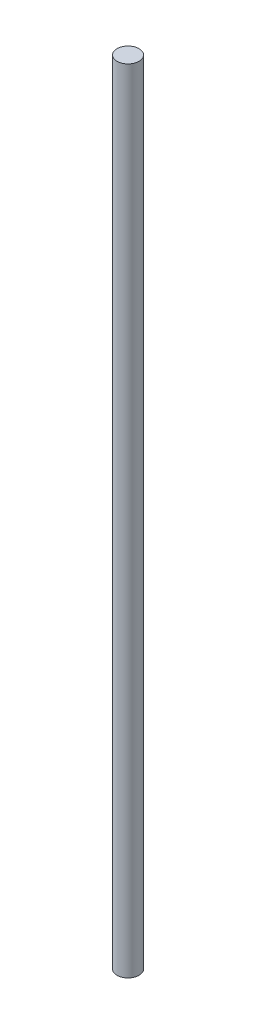
SolidWorks part; units mm, degrees
ref_plane "Спереди" through (0, 0, 0) normal (0, 0, 1) x (1, 0, 0)
ref_plane "Сверху" through (0, 0, 0) normal (0, 1, 0) x (1, 0, 0)
ref_plane "Справа" through (0, 0, 0) normal (1, 0, 0) x (0, 0, -1)
sketch "Эскиз1" plane through (0, 0, 0) normal (0, 1, 0) x (1, 0, 0)
  circle A0 centre (0, 0) radius 2.5
  dimension "D1" = 5
extrude "Бобышка-Вытянуть1" add sketch "Эскиз1" along normal blind 180
equation "\"motor_diameter\"= 30"
equation "\"mm_diameter\"= IIF ( \"motor_diameter\" < 34 , 41 , \"motor_diameter\" + 8 )"
equation "\"upper_shafts_diameter\"= 5"
equation "\"upper_shats_length\"= 180"
equation "\"upper_bearing_d1\"= 10"
equation "\"upper_bearing_d2\"= 5"
equation "\"upper_bearing_h\"= 15"
equation "\"lower_shafts_diameter\"= 5"
equation "\"lower_shafts_length\"= 180"
equation "\"lower_bearing_d1\"= 10"
equation "\"lower_bearing_d2\"= 5"
equation "\"lower_bearing_h\"= 15"
equation "\"print_offset\"= 0.5"
equation "\"bh_screws_d\"= 2"
equation "\"bh_screws_h\"= 20"
equation "\"bh_screws_hh_d\"= 3.4"
equation "\"bh_screws_hh_h\"= 2"
equation "\"bh_nut_d\"= 3.8"
equation "\"bh_nut_h\"= 2"
equation "\"motor_screws_d\"= 3"
equation "\"motor_screws_h\"= 16"
equation "\"motor_screws_hh_d\"= 5.5"
equation "\"motor_screws_hh_h\"= 3"
equation "\"plate_hole_distance\"= 25.4"
equation "\"plate_screws_d\"= 6.5"
equation "\"D1@Эскиз1\" = \"upper_shafts_diameter\""
equation "\"D1@Бобышка-Вытянуть1\"= \"upper_shats_length\""
